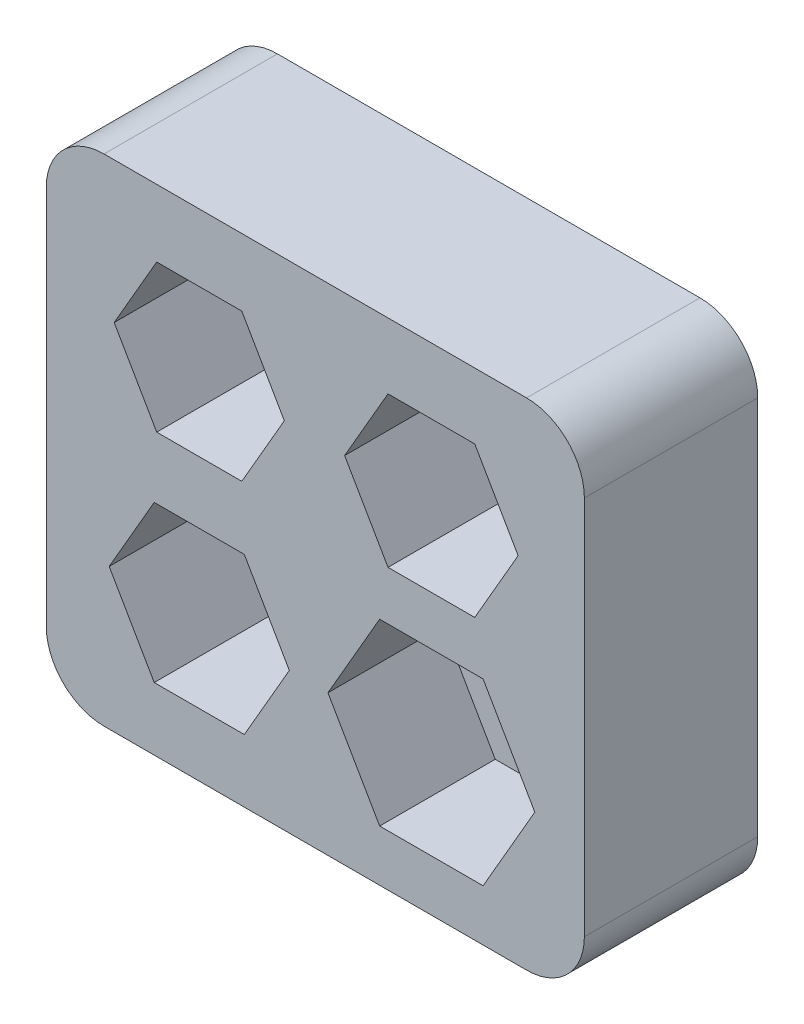
SolidWorks part; units mm, degrees
ref_plane "Front Plane" through (0, 0, 0) normal (0, 0, 1) x (1, 0, 0)
ref_plane "Top Plane" through (0, 0, 0) normal (0, 1, 0) x (1, 0, 0)
ref_plane "Right Plane" through (0, 0, 0) normal (1, 0, 0) x (0, 0, -1)
sketch "Sketch1" plane through (0, 0, 0) normal (0, 0, 1) x (1, 0, 0)
  line L0 (-2.0083, 1.8495) -> (-2.0083, -1.8495) construction
  line L1 (4.6558, -4.2877) -> (-4.6558, -4.2877)
  line L2 (4.6558, -4.2877) -> (4.6558, 4.2877)
  line L3 (4.6558, 4.2877) -> (-4.6558, 4.2877)
  line L4 (-4.6558, -4.2877) -> (-4.6558, 4.2877)
  line L5 (4.6558, -4.2877) -> (-4.6558, 4.2877) construction
  line L6 (4.6558, 4.2877) -> (-4.6558, -4.2877) construction
  line L7 (-2.7444, 3.1245) -> (-3.4805, 1.8495)
  line L8 (-3.4805, 1.8495) -> (-2.7444, 0.5745)
  line L9 (-2.7444, 0.5745) -> (-1.2722, 0.5745)
  line L10 (-1.2722, 0.5745) -> (-0.536, 1.8495)
  line L11 (-0.536, 1.8495) -> (-1.2722, 3.1245)
  line L12 (-1.2722, 3.1245) -> (-2.7444, 3.1245)
  line L13 (-2.0083, -1.8495) -> (2.0083, -1.8495) construction
  line L14 (2.0083, -1.8495) -> (2.0083, 1.8495) construction
  line L15 (2.0083, 1.8495) -> (-2.0083, 1.8495) construction
  line L17 (1.2577, 3.1495) -> (0.5072, 1.8495)
  line L18 (0.5072, 1.8495) -> (1.2577, 0.5495)
  line L19 (1.2577, 0.5495) -> (2.7588, 0.5495)
  line L20 (2.7588, 0.5495) -> (3.5094, 1.8495)
  line L21 (3.5094, 1.8495) -> (2.7588, 3.1495)
  line L22 (2.7588, 3.1495) -> (1.2577, 3.1495)
  line L23 (-2.7877, -0.4995) -> (-3.5671, -1.8495)
  line L24 (-3.5671, -1.8495) -> (-2.7877, -3.1995)
  line L25 (-2.7877, -3.1995) -> (-1.2289, -3.1995)
  line L26 (-1.2289, -3.1995) -> (-0.4494, -1.8495)
  line L27 (-0.4494, -1.8495) -> (-1.2289, -0.4995)
  line L28 (-1.2289, -0.4995) -> (-2.7877, -0.4995)
  line L29 (1.1134, -0.2995) -> (0.2185, -1.8495)
  line L30 (0.2185, -1.8495) -> (1.1134, -3.3995)
  line L31 (1.1134, -3.3995) -> (2.9032, -3.3995)
  line L32 (2.9032, -3.3995) -> (3.7981, -1.8495)
  line L33 (3.7981, -1.8495) -> (2.9032, -0.2995)
  line L34 (2.9032, -0.2995) -> (1.1134, -0.2995)
  circle A0 centre (-2.0083, 1.8495) radius 1.275 construction
  circle A1 centre (2.0083, 1.8495) radius 1.3 construction
  circle A2 centre (-2.0083, -1.8495) radius 1.35 construction
  circle A3 centre (2.0083, -1.8495) radius 1.55 construction
  point P0 (0, 0)
  point P17 (4.6558, -4.2877)
  dimension "D1" = 2.55
  dimension "D2" = 2.6
  dimension "D3" = 2.7
  dimension "D4" = 3.1
extrude "Boss-Extrude1" add sketch "Sketch1" along normal blind 2
sketch "Sketch2" plane through (0, 0, 0) normal (0, 0, -1) x (-1, 0, 0)
  line L1 (-4.6558, -4.2877) -> (4.6558, -4.2877)
  line L2 (-4.6558, -4.2877) -> (-4.6558, 4.2877)
  line L3 (-4.6558, 4.2877) -> (4.6558, 4.2877)
  line L4 (4.6558, -4.2877) -> (4.6558, 4.2877)
  line L5 (-4.6558, -4.2877) -> (4.6558, 4.2877) construction
  line L6 (-4.6558, 4.2877) -> (4.6558, -4.2877) construction
  point P0 (0, 0)
extrude "Boss-Extrude2" add sketch "Sketch2" along normal blind 1
sketch "Sketch3" plane through (0, 0, 0) normal (0, 0, 1) x (1, 0, 0)
  line L0 (-3.4805, 1.8495) -> (3.5094, 1.8495) construction
  line L1 (-3.5671, -1.8495) -> (3.7981, -1.8495) construction
  text T0 "    0,05               0,1" font "Century Gothic" height 0.5
extrude "Cut-Extrude1" cut sketch "Sketch3" against normal blind 0.5
sketch "Sketch4" plane through (0, 0, 0) normal (0, 0, 1) x (1, 0, 0)
  line L0 (-3.5617, -1.8589) -> (3.7926, -1.8589) construction
  line L1 (-3.5671, -1.8495) -> (-2.7877, -3.1995) construction
  line L2 (2.9032, -3.3995) -> (3.7981, -1.8495) construction
  text T0 "     0,2                0,5" font "Century Gothic" height 0.5
extrude "Cut-Extrude2" cut sketch "Sketch4" against normal blind 0.5
fillet "Fillet1" radius 1 4 edges at (-4.6558, -4.2877, 0.5) (4.6558, -4.2877, 0.5) (4.6558, 4.2877, 0.5) (-4.6558, 4.2877, 0.5)
